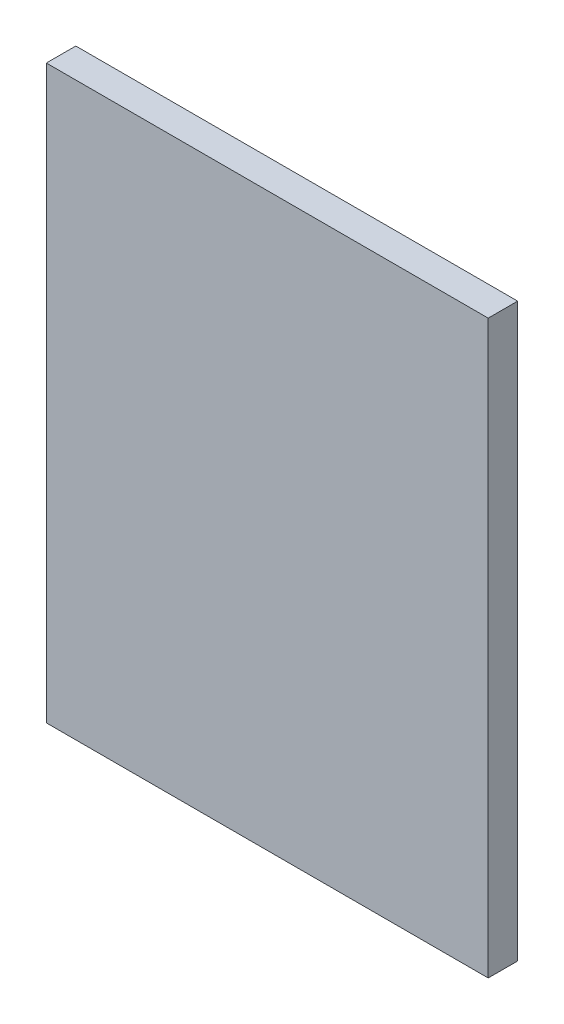
SolidWorks part; units mm, degrees
material "Silicon Dioxide"
ref_plane "Front Plane" through (0, 0, 0) normal (0, 0, 1) x (1, 0, 0)
ref_plane "Top Plane" through (0, 0, 0) normal (0, 1, 0) x (1, 0, 0)
ref_plane "Right Plane" through (0, 0, 0) normal (1, 0, 0) x (0, 0, -1)
sketch "Sketch1" plane through (0, 0, 0) normal (0, 0, 1) x (1, 0, 0)
  line L1 (-75.6362, 48.0134) -> (-0.6362, 48.0134)
  line L2 (-75.6362, 48.0134) -> (-75.6362, -48.9866)
  line L3 (-75.6362, -48.9866) -> (-0.6362, -48.9866)
  line L4 (-0.6362, 48.0134) -> (-0.6362, -48.9866)
  dimension "D1" = 75
  dimension "D2" = 97
extrude "Boss-Extrude1" add sketch "Sketch1" along normal blind 5
